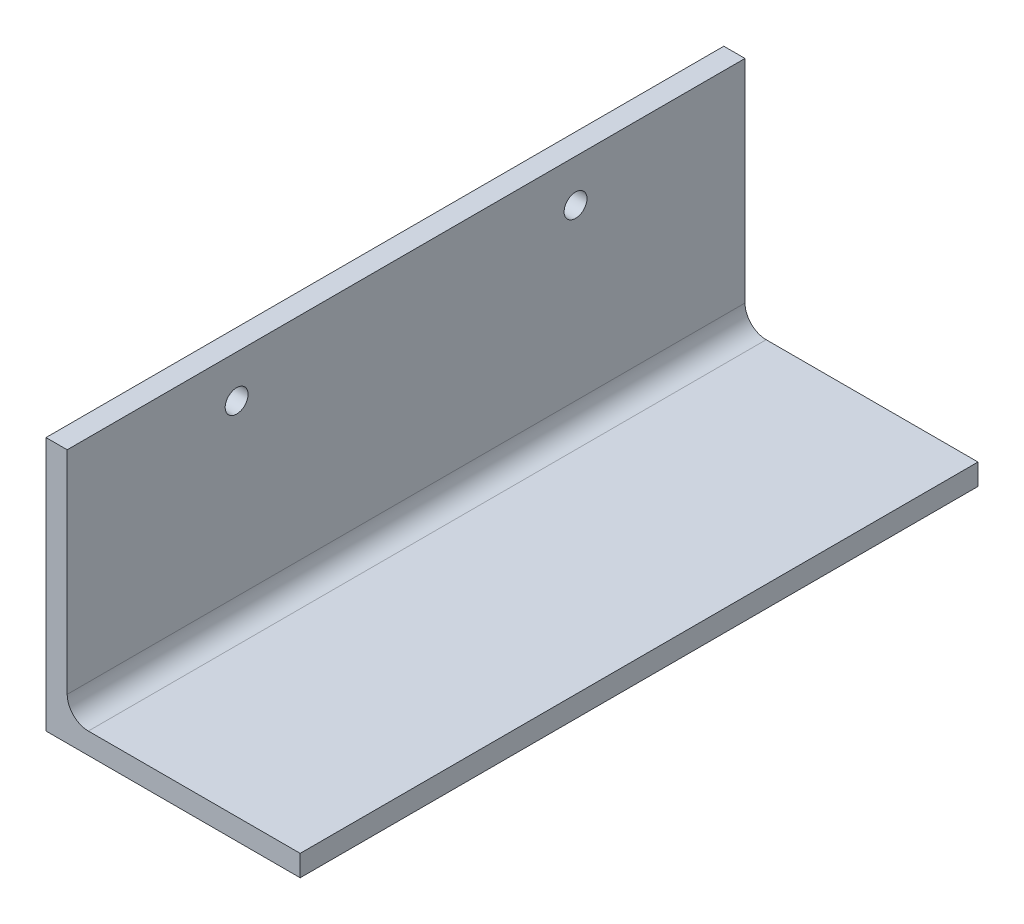
SolidWorks part; units mm, degrees
material "1060 Alloy"
ref_plane "Front Plane" through (0, 0, 0) normal (0, 0, 1) x (1, 0, 0)
ref_plane "Top Plane" through (0, 0, 0) normal (0, 1, 0) x (1, 0, 0)
ref_plane "Right Plane" through (0, 0, 0) normal (1, 0, 0) x (0, 0, -1)
sketch "Sketch1" plane through (0, 0, 0) normal (0, 0, 1) x (1, 0, 0)
  line L0 (0, 0) -> (76.2, 0)
  line L1 (76.2, 0) -> (76.2, 6.35)
  line L2 (76.2, 6.35) -> (12.7, 6.35)
  line L3 (6.35, 12.7) -> (6.35, 76.2)
  line L4 (6.35, 76.2) -> (0, 76.2)
  line L5 (0, 76.2) -> (0, 0)
  arc A0 (12.7, 6.35) -> (6.35, 12.7) centre (12.7, 12.7) cw
  dimension "D3" = 6.35
  dimension "D1" = 76.2
  dimension "D2" = 6.35
extrude "Boss-Extrude1" add sketch "Sketch1" along normal blind 203.2
sketch "Sketch2" plane through (6.35, 0, 0) normal (1, 0, 0) x (0, 0, -1)
  line L0 (-203.2, 0) -> (0, 0) construction
  line L1 (0, 12.7) -> (0, 76.2) construction
  circle A0 centre (-50.8, 63.5) radius 3.429
  circle A1 centre (-152.4, 63.5) radius 3.429
  dimension "D4" = 6.858
  dimension "D1" = 63.5
  dimension "D2" = 50.8
  dimension "D3" = 101.6
extrude "Cut-Extrude1" cut sketch "Sketch2" against normal through all
